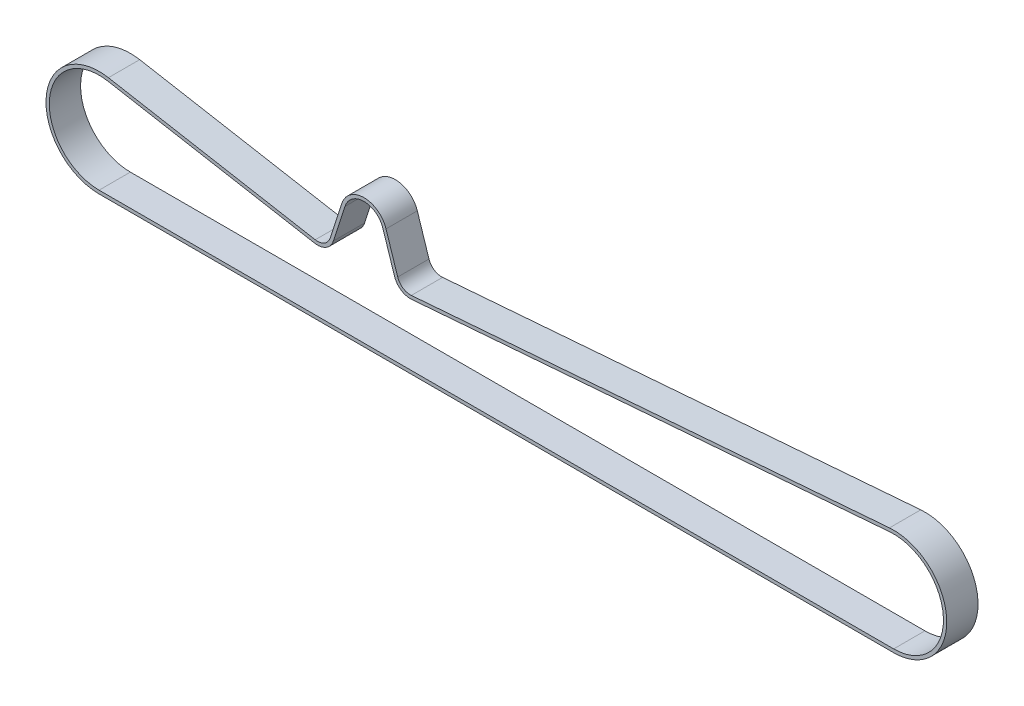
SolidWorks part; units mm, degrees
material "Rubber"
ref_plane "Front" through (0, 0, 0) normal (0, 0, 1) x (1, 0, 0)
ref_plane "Top" through (0, 0, 0) normal (0, 1, 0) x (1, 0, 0)
ref_plane "Right" through (0, 0, 0) normal (1, 0, 0) x (0, 0, -1)
sketch "Sketch1" plane through (0, 0, 0) normal (0, 0, 1) x (1, 0, 0)
  line L0 (235.8136, 0) -> (-235.8136, 0) construction
  line L1 (104.775, 13.6073) -> (149.225, 13.6073) construction
  line L2 (127, 25.4) -> (127, 13.6073) construction
  line L3 (0, -23.876) -> (381, -23.876)
  line L4 (379.1202, 23.8019) -> (149.8499, 5.6945)
  line L5 (141.6767, 11.1523) -> (136.0821, 28.3538)
  line L6 (117.9179, 28.3538) -> (112.3233, 11.1523)
  line L7 (103.3797, 5.7934) -> (4.1971, 23.5042)
  line L8 (103.6588, 7.3562) -> (4.4761, 25.067)
  line L9 (0, -25.4635) -> (381, -25.4635)
  line L10 (378.9952, 25.3845) -> (149.725, 7.277)
  line L11 (143.1864, 11.6433) -> (137.5918, 28.8448)
  line L12 (116.4082, 28.8448) -> (110.8136, 11.6433)
  circle A0 centre (0, 0) radius 23.876 construction
  circle A1 centre (381, 0) radius 23.876 construction
  circle A2 centre (127, 25.4) radius 9.5504 construction
  circle A3 centre (104.775, 13.6073) radius 7.9375 construction
  circle A4 centre (149.225, 13.6073) radius 7.9375 construction
  arc A5 (103.3797, 5.7934) -> (112.3233, 11.1523) centre (104.775, 13.6073) ccw
  arc A6 (117.9179, 28.3538) -> (136.0821, 28.3538) centre (127, 25.4) cw
  arc A7 (141.6767, 11.1523) -> (149.8499, 5.6945) centre (149.225, 13.6073) ccw
  arc A8 (379.1202, 23.8019) -> (381, -23.876) centre (381, 0) cw
  arc A9 (4.1971, 23.5042) -> (0, -23.876) centre (0, 0) ccw
  arc A10 (4.4761, 25.067) -> (0, -25.4635) centre (0, 0) ccw
  arc A11 (378.9952, 25.3845) -> (381, -25.4635) centre (381, 0) cw
  arc A12 (143.1864, 11.6433) -> (149.725, 7.277) centre (149.225, 13.6073) ccw
  arc A13 (116.4082, 28.8448) -> (137.5918, 28.8448) centre (127, 25.4) cw
  arc A14 (103.6588, 7.3562) -> (110.8136, 11.6433) centre (104.775, 13.6073) ccw
  dimension "D1" = 47.752
  dimension "D3" = 19.1008
  dimension "D4" = 15.875
  dimension "D5" = 44.45
  dimension "35.433" = 950.0006
  dimension "D2" = 25.4
  dimension "D6" = 381
  dimension "D7" = 1.5875
  dimension "D8" = 127
extrude "Boss-Extrude1" add sketch "Sketch1" along normal mid plane 15
